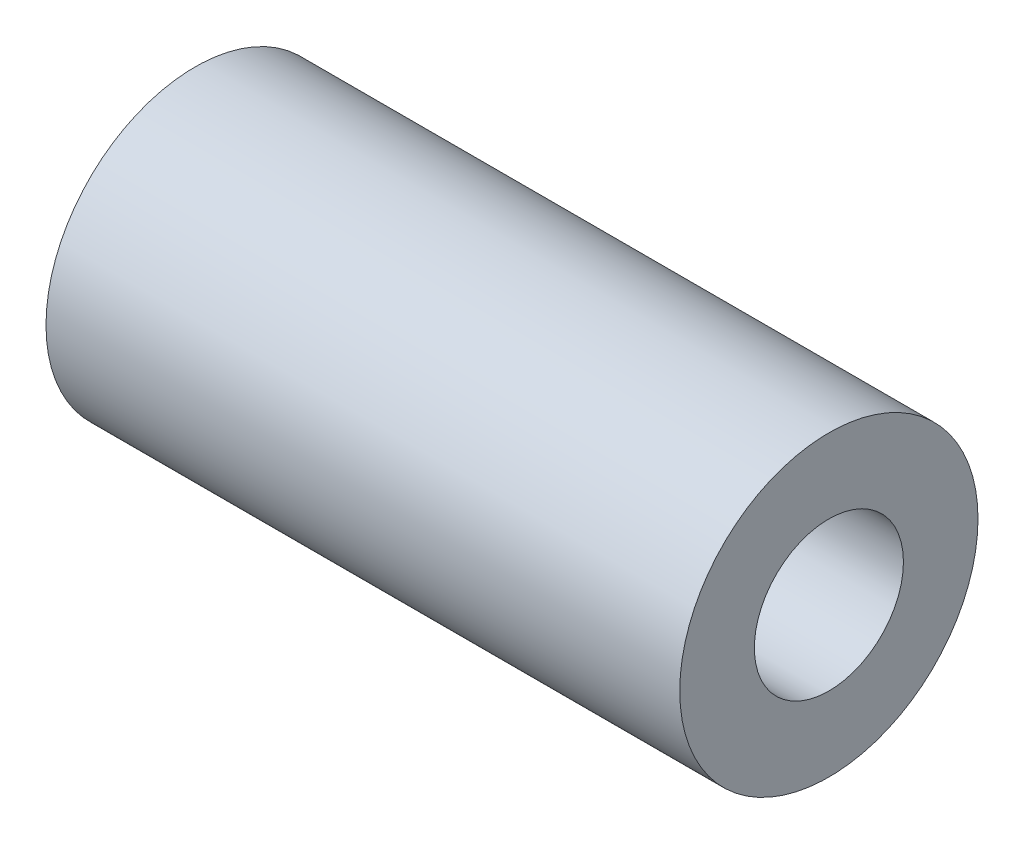
SolidWorks part; units mm, degrees
ref_plane "Front Plane" through (0, 0, 0) normal (0, 0, 1) x (1, 0, 0)
ref_plane "Top Plane" through (0, 0, 0) normal (0, 1, 0) x (1, 0, 0)
ref_plane "Right Plane" through (0, 0, 0) normal (1, 0, 0) x (0, 0, -1)
sketch "Sketch1" plane through (0, 0, 0) normal (1, 0, 0) x (0, 0, -1)
  circle A0 centre (0, 0) radius 3.175
  circle A1 centre (0, 0) radius 6.35
  dimension "D1" = 6.35
  dimension "D2" = 12.7
extrude "Boss-Extrude1" add sketch "Sketch1" along normal blind 26.9875
